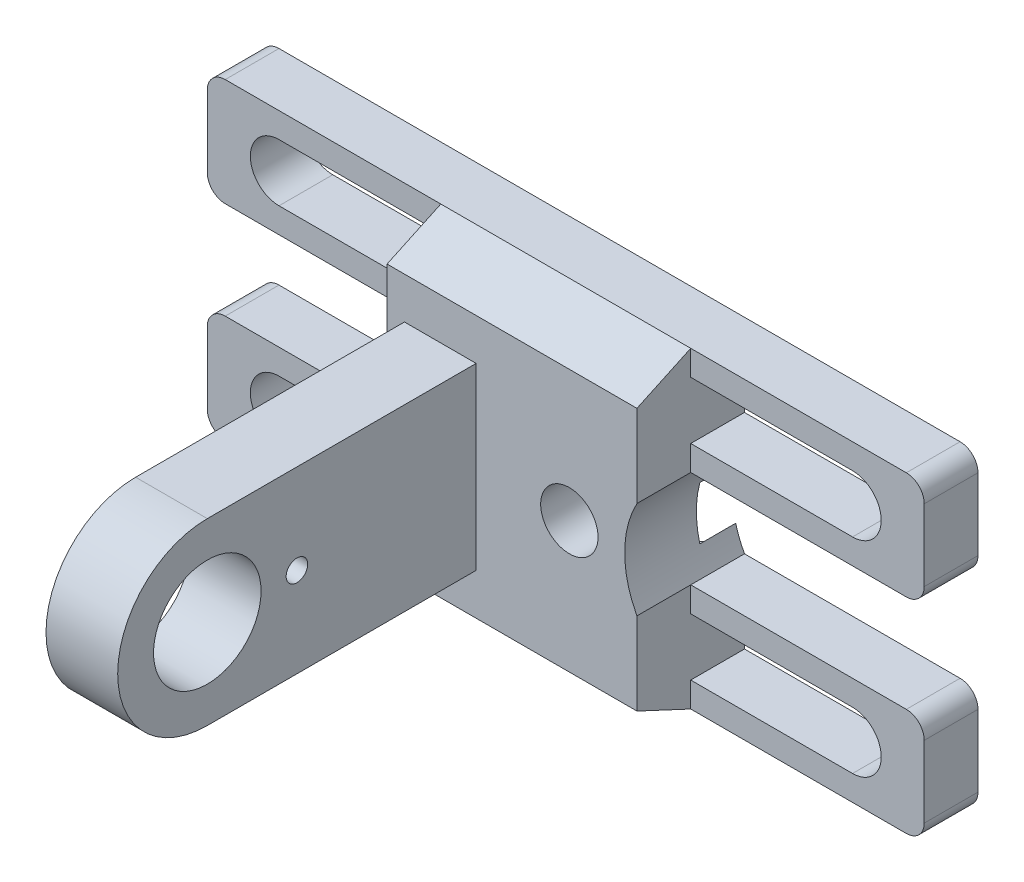
SolidWorks part; units mm, degrees
ref_plane "前视基准面" through (0, 0, 0) normal (0, 0, 1) x (1, 0, 0)
ref_plane "上视基准面" through (0, 0, 0) normal (0, 1, 0) x (1, 0, 0)
ref_plane "右视基准面" through (0, 0, 0) normal (1, 0, 0) x (0, 0, -1)
other "Configuration Table"
sketch "草图1" plane through (0, 0, 0) normal (0, 0, 1) x (1, 0, 0)
  line L0 (30.1537, 0) -> (-30.0932, 0) construction
  line L1 (0, -18.3903) -> (0, 24.264) construction
  line L2 (20, 8.715) -> (20, 2.715)
  line L3 (20, 8.715) -> (-20, 8.715)
  line L5 (20, 2.715) -> (6.9711, 2.715)
  line L6 (-20, 8.715) -> (-20, 2.715)
  line L7 (-20, -8.715) -> (-20, -2.715)
  line L8 (20, -2.715) -> (6.9711, -2.715)
  line L9 (20, -8.715) -> (-20, -8.715)
  line L10 (20, -8.715) -> (20, -2.715)
  line L11 (20, 5.715) -> (-20, 5.715) construction
  line L12 (20, -5.715) -> (-20, -5.715) construction
  line L13 (16, 5.715) -> (-16, 5.715) construction
  line L14 (16, 4.115) -> (-16, 4.115)
  line L15 (16, 7.315) -> (-16, 7.315)
  line L16 (16, -5.715) -> (-16, -5.715) construction
  line L17 (16, -7.315) -> (-16, -7.315)
  line L18 (16, -4.115) -> (-16, -4.115)
  line L21 (-6.9711, 2.715) -> (-20, 2.715)
  line L22 (-6.9711, -2.715) -> (-20, -2.715)
  arc A0 (16, 4.115) -> (16, 7.315) centre (16, 5.715) ccw
  arc A1 (-16, 7.315) -> (-16, 4.115) centre (-16, 5.715) ccw
  arc A2 (16, -7.315) -> (16, -4.115) centre (16, -5.715) ccw
  arc A3 (-16, -4.115) -> (-16, -7.315) centre (-16, -5.715) ccw
  arc A4 (-6.9711, -2.715) -> (-6.9711, 2.715) centre (-12, 0) ccw
  arc A5 (6.9711, -2.715) -> (6.9711, 2.715) centre (12, 0) cw
  point P19 (0, 5.715)
  point P26 (0, -5.715)
  point P37 (0, 2.715)
  point P38 (0, -2.715)
  dimension "D8" = 12
  dimension "D1" = 6
  dimension "D2" = 40
  dimension "D3" = 32
  dimension "D4" = 3.2
  dimension "D5" = 3.2
  dimension "D6" = 32
  dimension "D7" = 11.43
extrude "凸台-拉伸1" add sketch "草图1" along normal blind 3
sketch "草图2" plane through (0, 0, 3) normal (0, 0, 1) x (1, 0, 0)
  line L2 (-16, 4.115) -> (16, 4.115) construction
  line L4 (-6.9711, 2.715) -> (-6.9711, 4.115)
  line L6 (6.9711, 2.715) -> (6.9711, 4.115)
  line L7 (16, -4.115) -> (-16, -4.115) construction
  line L9 (-6.9711, -2.715) -> (-6.9711, -4.115)
  line L11 (6.9711, -2.715) -> (6.9711, -4.115)
  line L12 (-6.9711, 4.115) -> (-6.9711, 7.315)
  line L13 (16, 7.315) -> (-16, 7.315) construction
  line L14 (-6.9711, 7.315) -> (6.9711, 7.315)
  line L15 (6.9711, 7.315) -> (6.9711, 4.115)
  line L16 (6.9711, -4.115) -> (6.9711, -7.315)
  line L17 (-16, -7.315) -> (16, -7.315) construction
  line L18 (6.9711, -7.315) -> (-6.9711, -7.315)
  line L19 (-6.9711, -7.315) -> (-6.9711, -4.115)
  arc A0 (6.9711, 2.715) -> (6.9711, -2.715) centre (12, 0) ccw construction
  arc A1 (-6.9711, -2.715) -> (-6.9711, 2.715) centre (-12, 0) ccw construction
  arc A2 (6.9711, 2.715) -> (6.9711, -2.715) centre (12, 0) ccw
  arc A3 (-6.9711, -2.715) -> (-6.9711, 2.715) centre (-12, 0) ccw
extrude "凸台-拉伸2" add sketch "草图2" along normal blind 3 and the other way up to surface
sketch "草图3" plane through (0, 0, 0) normal (1, 0, 0) x (0, 0, -1)
  line L0 (1.8549, 0) -> (-13.3199, 0) construction
  line L1 (-6, 5) -> (-21, 5)
  line L2 (-6, 2.715) -> (-6, -2.715) construction
  line L4 (-6, 0) -> (0, 0) construction
  line L5 (-6, -5) -> (-21, -5)
  line L6 (-6, 5) -> (-6, -5)
  arc A0 (-21, 5) -> (-21, -5) centre (-21, 0) ccw
  circle A1 centre (-21, 0) radius 3
  circle A2 centre (-16, 0) radius 0.6
  dimension "D3" = 6
  dimension "D4" = 15
  dimension "D5" = 1.2
  dimension "D6" = 5
  dimension "D1" = 5
  dimension "D2" = 15
extrude "凸台-拉伸3" add sketch "草图3" against normal blind 4 from offset 2 offset against normal yes
sketch "草图5" plane through (0, 0, 0) normal (0, 0, -1) x (-1, 0, 0)
  line L0 (-6.9711, 2.715) -> (-12, 2.715)
  line L1 (-6.9711, 2.715) -> (-20, 2.715) construction
  line L2 (-12, 2.715) -> (-12, -2.715)
  line L3 (-20, -2.715) -> (-6.9711, -2.715) construction
  line L4 (-12, -2.715) -> (-6.9711, -2.715)
  line L5 (6.9711, 2.715) -> (12, 2.715)
  line L6 (20, 2.715) -> (6.9711, 2.715) construction
  line L7 (12, 2.715) -> (12, -2.715)
  line L8 (6.9711, -2.715) -> (20, -2.715) construction
  line L9 (12, -2.715) -> (6.9711, -2.715)
  arc A0 (-6.9711, -2.715) -> (-6.9711, 2.715) centre (-12, 0) ccw construction
  arc A1 (-6.9711, -2.715) -> (-6.9711, 2.715) centre (-12, 0) ccw
  arc A2 (6.9711, 2.715) -> (6.9711, -2.715) centre (12, 0) ccw construction
  arc A3 (6.9711, 2.715) -> (6.9711, -2.715) centre (12, 0) ccw
fillet "圆角2" radius 1 8 edges at (-20, 8.715, 1.5) (-20, 2.715, 1.5) (-20, -2.715, 1.5) (-20, -8.715, 1.5) (20, -8.715, 1.5) (20, -2.715, 1.5) (20, 2.715, 1.5) (20, 8.715, 1.5)
sketch "草图6" plane through (6.9711, 0, 0) normal (1, 0, 0) x (0, 0, -1)
  line L0 (-6, 7.315) -> (-3, 8.715)
  line L1 (-3, 8.715) -> (-3, 7.315)
  line L2 (-3, 7.315) -> (-6, 7.315)
  line L3 (3.4836, 0) -> (-14.6957, 0) construction
  line L4 (-3, -7.315) -> (-6, -7.315)
  line L5 (-3, -8.715) -> (-3, -7.315)
  line L6 (-6, -7.315) -> (-3, -8.715)
extrude "凸台-拉伸4" add sketch "草图6" against normal up to surface (13.9422 mm away) up to face at (-6.9711, 5.0864, 3)
sketch "草图7" plane through (-6, 0, 0) normal (-1, 0, 0) x (0, 0, 1)
  line L0 (21, -5) -> (6, -5) construction
  line L1 (6, 5) -> (9, 5)
  line L2 (6, 5) -> (6, -5)
  line L3 (6, -5) -> (9, -5)
  line L4 (9, 5) -> (9, -5)
  dimension "D1" = 3
extrude "凸台-拉伸5" [suppressed] add sketch "草图7" along normal blind 20
sketch "草图8" plane through (0, 0, 6) normal (0, 0, 1) x (1, 0, 0)
  line L0 (-15.4397, 0) -> (23.6043, 0) construction
  line L1 (-2, -5) -> (-2, 5) construction
  circle A0 centre (3.2, 0) radius 1.6
  dimension "D1" = 3.2
  dimension "D2" = 5.2
extrude "切除-拉伸1" cut sketch "草图8" against normal through all
sketch "草图9" plane through (0, 0, 0) normal (0, 0, -1) x (-1, 0, 0)
  circle A0 centre (-3.2, 0) radius 3.6
  dimension "D1" = 7.2
extrude "切除-拉伸2" cut sketch "草图9" against normal blind 2
